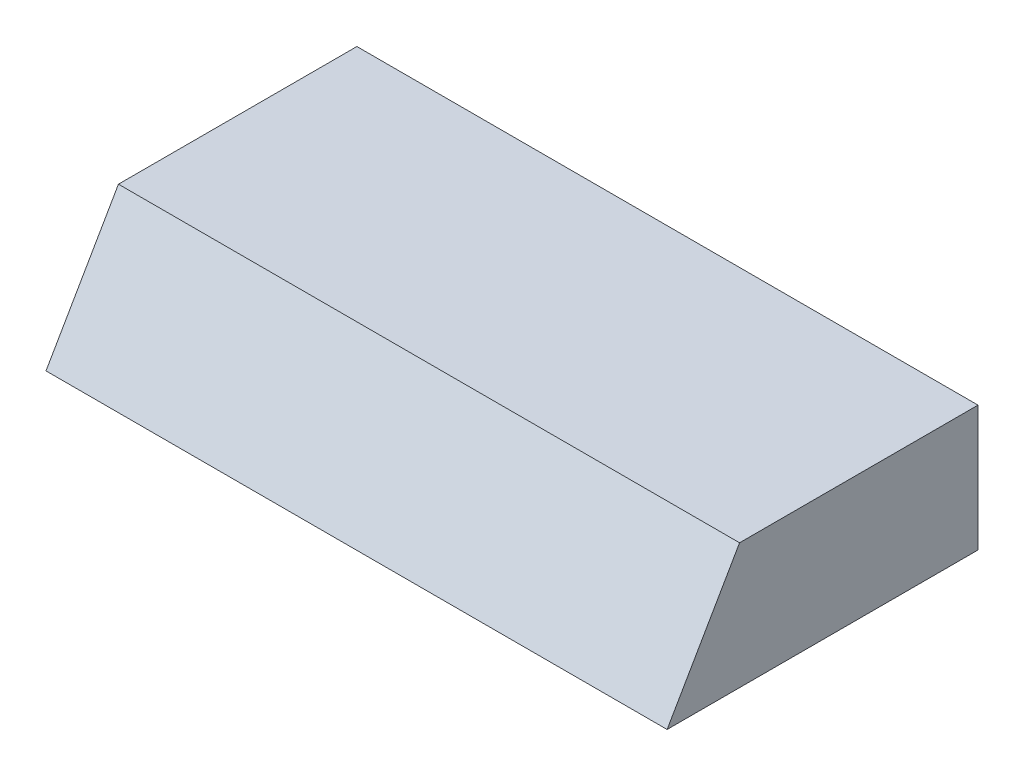
SolidWorks part; units mm, degrees
ref_plane "Alzado" through (0, 0, 0) normal (0, 0, 1) x (1, 0, 0)
ref_plane "Planta" through (0, 0, 0) normal (0, 1, 0) x (1, 0, 0)
ref_plane "Vista lateral" through (0, 0, 0) normal (1, 0, 0) x (0, 0, -1)
sketch "Sketch1" plane through (0, 0, 0) normal (1, 0, 0) x (0, 0, -1)
  line L0 (22.1085, 0) -> (32.4418, 17.8992)
  line L3 (-73.8644, -51.971) -> (121.1356, -51.9647) construction
  line L4 (22.1085, 0) -> (121.18, 0)
  line L5 (121.18, 0) -> (121.2142, 40)
  line L6 (45.2007, 40) -> (121.2142, 40)
  line L7 (32.4418, 17.8992) -> (45.2007, 40)
  line L8 (121.1356, -51.9647) -> (121.18, 0) construction
  dimension "D1" = 120
  dimension "D2" = 40
  dimension "D3" = 120
  dimension "D4" = 76.0135
extrude "Boss-Extrude1" add sketch "Sketch1" along normal blind 198
shell "Shell1" thickness 7
sketch "Sketch2" plane through (0, 0, 0) normal (-1, 0, 0) x (0, 0, 1)
  line L0 (-30.1912, 0) -> (-32.9749, 0)
  line L1 (-32.9749, 0) -> (-52.026, 33)
  line L2 (73.8644, -51.971) -> (-121.1356, -51.9647) construction
  line L3 (-52.026, 33) -> (-49.2423, 33)
  line L4 (-49.2423, 33) -> (-30.1912, 0)
  dimension "D1" = 120
extrude "Boss-Extrude2" add sketch "Sketch2" against normal blind 191
sketch "Sketch3" plane through (0, 0, 0) normal (-1, 0, 0) x (0, 0, 1)
  line L0 (-45.2007, 40) -> (-22.1085, 0) construction
  line L1 (-121.18, 0) -> (-25.9344, 0)
  line L2 (-121.18, 0) -> (-121.18, 3)
  line L3 (-121.18, 3) -> (-25.9344, 3)
  line L4 (-25.9344, 0) -> (-25.9344, 3)
  line L5 (-121.2142, 40) -> (-45.2007, 40) construction
  dimension "D1" = 95.2456
  dimension "D2" = 3
  dimension "D3" = 150.002
  dimension "D4" = 37
extrude "Boss-Extrude3" add sketch "Sketch3" against normal blind 191
sketch "Sketch4" plane through (0, 3, 0) normal (0, 1, 0) x (1, 0, 0)
  line L0 (191, 114.1826) -> (7, 114.1826) construction
  line L1 (7, 114.1826) -> (7, 34.7068) construction
  line L3 (7, 34.7068) -> (191, 34.7068) construction
  circle A0 centre (11, 109.1826) radius 1.585
  circle A1 centre (11, 39.7068) radius 1.585
  dimension "D1" = 3.17
  dimension "D4" = 3.17
  dimension "D2" = 5
  dimension "D3" = 4
  dimension "D5" = 5
  dimension "D6" = 4
extrude "Cut-Extrude1" cut sketch "Sketch4" against normal blind 5
ref_plane "Plane1" through (99, 0, 0) normal (1, 0, 0) x (0, 0, -1)
mirror "Mirror1" about plane through (99, 0, 0) normal (1, 0, 0) of "Cut-Extrude1"
sketch "Sketch5" plane through (0, 3, 0) normal (0, 1, 0) x (1, 0, 0)
  line L0 (191, 34.7068) -> (191, 114.1826) construction
  line L1 (187.2466, 56.4996) -> (77.2466, 56.4734)
  line L2 (187.2466, 56.4996) -> (187.2609, 91.4996)
  line L3 (187.2609, 91.4996) -> (77.2609, 91.4734)
  line L4 (77.2466, 56.4734) -> (77.2609, 91.4734)
  line L5 (191, 114.1826) -> (7, 114.1826) construction
  point P4 (116.3414, 63.1798)
  point P5 (226.3405, 28.1798)
  dimension "D1" = 35
  dimension "D2" = 110
  dimension "D3" = 110
  dimension "D4" = 35
  dimension "D5" = 179.976
  dimension "D6" = 0.014
extrude "Boss-Extrude4" add sketch "Sketch5" along normal blind 25
